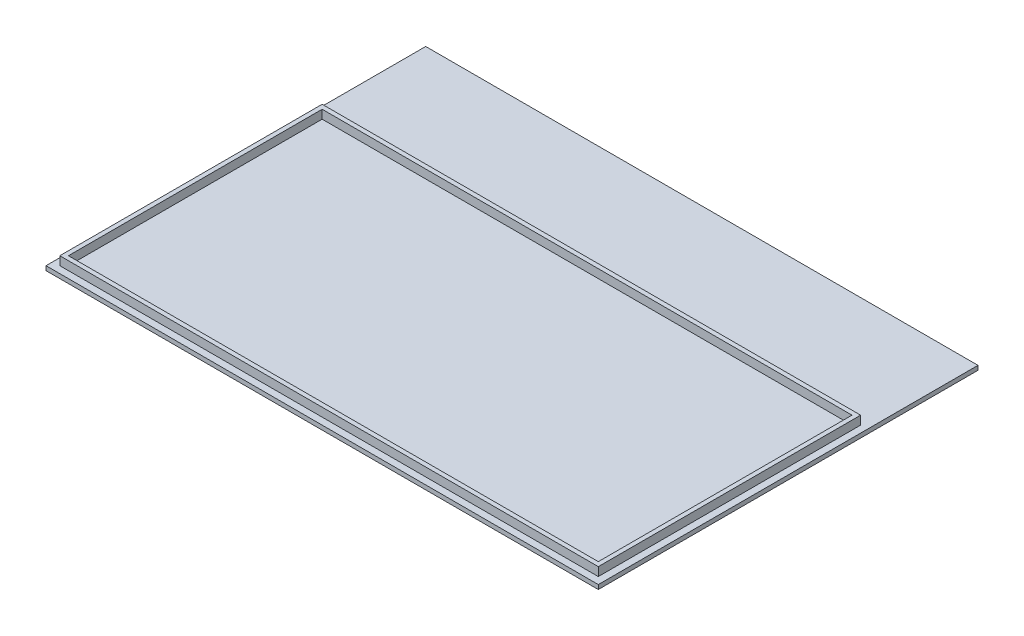
SolidWorks part; units mm, degrees
ref_plane "Front Plane" through (0, 0, 0) normal (0, 0, 1) x (1, 0, 0)
ref_plane "Top Plane" through (0, 0, 0) normal (0, 1, 0) x (1, 0, 0)
ref_plane "Right Plane" through (0, 0, 0) normal (1, 0, 0) x (0, 0, -1)
sketch "Sketch1" plane through (0, 0, 0) normal (0, 1, 0) x (1, 0, 0)
  line L1 (-101.6, -50.8) -> (101.6, -50.8)
  line L2 (-101.6, -50.8) -> (-101.6, 50.8)
  line L3 (-101.6, 50.8) -> (101.6, 50.8)
  line L4 (101.6, -50.8) -> (101.6, 50.8)
  line L5 (-101.6, -50.8) -> (101.6, 50.8) construction
  line L6 (-101.6, 50.8) -> (101.6, -50.8) construction
  point P0 (0, 0)
  dimension "D1" = 203.2
  dimension "D2" = 101.6
extrude "Boss-Extrude1" add sketch "Sketch1" along normal blind 1.5875
sketch "Sketch2" plane through (0, 1.5875, 0) normal (0, 1, 0) x (1, 0, 0)
  line L0 (-101.6, 50.8) -> (-101.6, -50.8) construction
  line L1 (-99.06, 48.26) -> (99.06, 48.26)
  line L2 (-99.06, 48.26) -> (-99.06, -48.26)
  line L3 (-99.06, -48.26) -> (99.06, -48.26)
  line L4 (99.06, 48.26) -> (99.06, -48.26)
  line L5 (101.6, 50.8) -> (-101.6, 50.8) construction
  line L6 (101.6, -50.8) -> (101.6, 50.8) construction
  line L7 (-101.6, -50.8) -> (101.6, -50.8) construction
  dimension "D1" = 2.54
  dimension "D2" = 2.54
  dimension "D3" = 2.54
  dimension "D4" = 2.54
  dimension "D5" = 198.12
  dimension "D6" = 96.52
extrude "Boss-Extrude2" add sketch "Sketch2" along normal blind 3.175
sketch "Sketch3" plane through (0, 4.7625, 0) normal (0, 1, 0) x (1, 0, 0)
  line L0 (-99.06, 48.26) -> (-99.06, -48.26) construction
  line L1 (-97.4725, 46.6725) -> (97.4725, 46.6725)
  line L2 (-97.4725, 46.6725) -> (-97.4725, -46.6725)
  line L3 (-97.4725, -46.6725) -> (97.4725, -46.6725)
  line L4 (97.4725, 46.6725) -> (97.4725, -46.6725)
  line L5 (99.06, 48.26) -> (-99.06, 48.26) construction
  line L6 (99.06, -48.26) -> (99.06, 48.26) construction
  line L7 (-99.06, -48.26) -> (99.06, -48.26) construction
  dimension "D1" = 1.5875
  dimension "D2" = 1.5875
  dimension "D3" = 1.5875
  dimension "D4" = 1.5875
extrude "Cut-Extrude1" cut sketch "Sketch3" against normal blind 3.175
sketch "Sketch5" plane through (0, 0, -50.8) normal (0, 0, -1) x (-1, 0, 0)
  line L1 (-101.6, 1.5875) -> (101.6, 1.5875)
  line L2 (-101.6, 1.5875) -> (-101.6, 0)
  line L3 (-101.6, 0) -> (101.6, 0)
  line L4 (101.6, 1.5875) -> (101.6, 0)
extrude "Boss-Extrude3" add sketch "Sketch5" along normal blind 38.1
